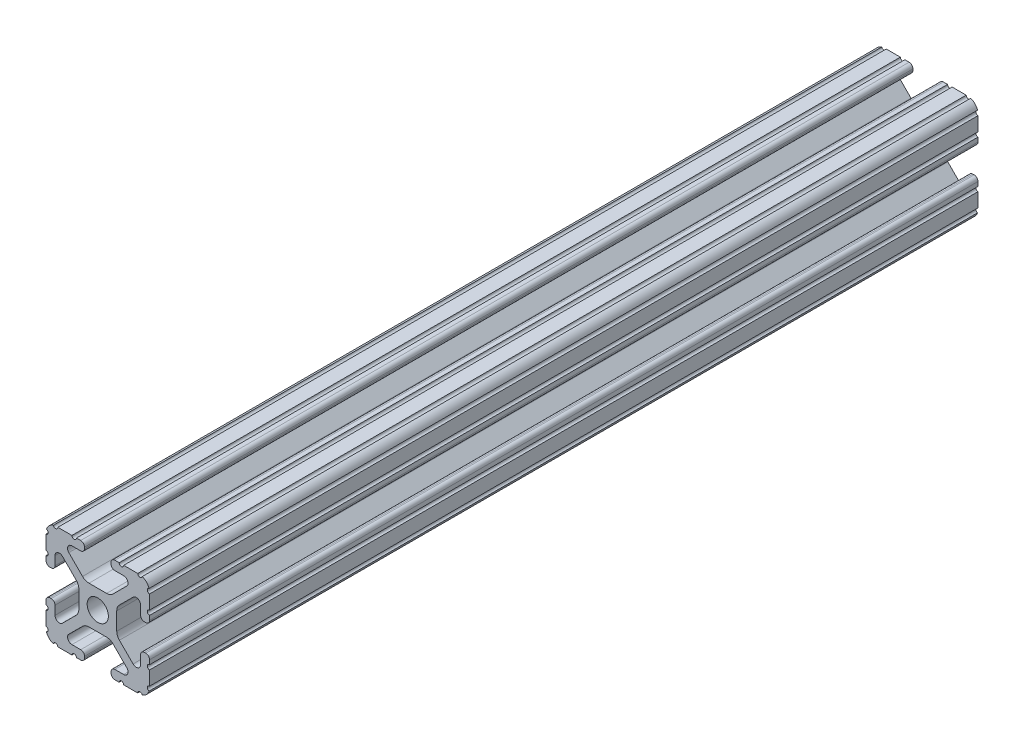
SolidWorks part; units mm, degrees
ref_plane "Front Plane" through (0, 0, 0) normal (0, 0, 1) x (1, 0, 0)
ref_plane "Top Plane" through (0, 0, 0) normal (0, 1, 0) x (1, 0, 0)
ref_plane "Right Plane" through (0, 0, 0) normal (1, 0, 0) x (0, 0, -1)
sketch "Sketch2" plane through (0, 0, 0) normal (0, 0, 1) x (1, 0, 0)
  line L0 (0, 12.7) -> (0, -12.7) construction
  line L1 (-12.7, 0) -> (12.7, 0) construction
  line L2 (3.2512, -12.7) -> (12.7, -12.7)
  line L3 (12.7, -12.7) -> (12.7, -3.2512)
  line L4 (3.2512, -12.7) -> (3.2512, -10.4902)
  line L5 (3.2512, -10.4902) -> (8.9276, -10.4902)
  line L6 (8.9276, -10.4902) -> (3.0856, -4.6482)
  line L7 (0, 0) -> (12.7, -12.7) construction
  line L8 (12.7, -3.2512) -> (10.4902, -3.2512)
  line L9 (10.4902, -3.2512) -> (10.4902, -8.9276)
  line L10 (10.4902, -8.9276) -> (4.6482, -3.0856)
  circle A0 centre (0, 0) radius 2.6035
  arc A1 (6.3485, -10.4902) -> (7.1039, -8.6665) centre (6.3485, -9.4219) ccw construction
  point P8 (0, -4.6482)
  dimension "Center Hole Diameter" = 5.207
  dimension "Rail Height" = 25.4
  dimension "Rail Width" = 25.4
  dimension "T-Slot Width" = 6.5024
  dimension "Slot Inner Width" = 14.8336
  dimension "Thickness" = 2.2098
  dimension "Slot Depth" = 5.842
  dimension "D1" = 2.2098
sketch "Sketch3" plane through (0, 0, 0) normal (1, 0, 0) x (0, 0, -1)
  line L0 (-152.4, -12.7) -> (152.4, -12.7) construction
  line L1 (-127, 0) -> (127, 0) construction
  dimension "Length" = 304.8
  dimension "D1" = 25.4
sketch "Sketch4" plane through (0, 0, 0) normal (0, 0, 1) x (1, 0, 0)
  line L0 (4.1904, -12.7) -> (10.1173, -12.7)
  line L1 (3.2512, -12.7) -> (12.7, -12.7) construction
  line L2 (3.2512, -12.7) -> (3.2512, -10.4902) construction
  line L3 (3.2512, -10.4902) -> (8.9276, -10.4902) construction
  line L4 (3.2512, -11.4294) -> (3.2512, -11.7608)
  line L5 (4.1904, -10.4902) -> (6.3485, -10.4902)
  line L6 (0, -4.6482) -> (2.164, -4.6482)
  line L7 (8.9276, -10.4902) -> (3.0856, -4.6482) construction
  line L8 (3.7373, -5.2999) -> (7.1039, -8.6665)
  line L9 (12.7, -12.7) -> (12.7, -3.2512) construction
  line L10 (10.4902, -8.9276) -> (4.6482, -3.0856) construction
  line L11 (10.4902, -3.2512) -> (10.4902, -8.9276) construction
  line L12 (10.4902, -6.3485) -> (10.4902, -4.1904)
  line L13 (12.7, -3.2512) -> (10.4902, -3.2512) construction
  line L14 (11.4294, -3.2512) -> (11.7608, -3.2512)
  line L15 (12.7, -4.1904) -> (12.7, -10.1173)
  line L16 (8.6665, -7.1039) -> (5.2999, -3.7373)
  line L17 (4.6482, 0) -> (4.6482, -2.164)
  line L18 (-12.7, 0) -> (12.7, 0) construction
  line L19 (0, -4.6482) -> (0, -2.6035)
  line L20 (0, 12.7) -> (0, -12.7) construction
  line L21 (4.6482, 0) -> (2.6035, 0)
  arc A0 (3.2512, -11.7608) -> (4.1904, -12.7) centre (4.1904, -11.7608) ccw
  arc A2 (3.2512, -11.4294) -> (4.1904, -10.4902) centre (4.1904, -11.4294) cw
  arc A3 (6.3485, -10.4902) -> (7.1039, -8.6665) centre (6.3485, -9.4219) ccw
  arc A4 (2.164, -4.6482) -> (3.7373, -5.2999) centre (2.164, -6.8732) cw
  arc A5 (10.1173, -12.7) -> (12.7, -10.1173) centre (10.1173, -10.1173) ccw
  arc A6 (8.6665, -7.1039) -> (10.4902, -6.3485) centre (9.4219, -6.3485) ccw
  arc A7 (10.4902, -4.1904) -> (11.4294, -3.2512) centre (11.4294, -4.1904) cw
  arc A8 (11.7608, -3.2512) -> (12.7, -4.1904) centre (11.7608, -4.1904) cw
  arc A9 (5.2999, -3.7373) -> (4.6482, -2.164) centre (6.8732, -2.164) cw
  circle A10 centre (0, 0) radius 2.6035 construction
  arc A11 (0, -2.6035) -> (2.6035, 0) centre (0, 0) ccw
  dimension "D1" = 2.5827
  dimension "D2" = 2.225
  dimension "D3" = 0.9392
extrude "Boss-Extrude1" add sketch "Sketch4" along normal mid plane 304.8
sketch "Sketch5" plane through (0, 0, 0) normal (0, 0, 1) x (1, 0, 0)
  line L0 (3.2512, -12.7) -> (12.7, -12.7) construction
  line L1 (4.1904, -10.4902) -> (6.3485, -10.4902) construction
  line L3 (0, 0) -> (12.7, -12.7) construction
  line L4 (6.3485, -10.4902) -> (6.3485, -12.7) construction
  line L5 (8.9276, -10.4902) -> (3.0856, -4.6482) construction
  circle A0 centre (10.3562, -12.7) radius 0.5524
  circle A1 centre (5.796, -12.7) radius 0.5524
  circle A2 centre (12.7, -10.3562) radius 0.5524
  circle A3 centre (12.7, -5.796) radius 0.5524
  point P10 (5.2694, -10.4902)
  point P12 (9.4219, -6.3485)
  dimension "D1" = 1.1049
extrude "Cut-Extrude1" cut sketch "Sketch5" against normal through all both and the other way through all
mirror "Mirror1" about plane through (0, 0, 0) normal (1, 0, 0) of bodies 137 134
mirror "Mirror2" about plane through (0, 0, 0) normal (0, 1, 0) of bodies 135
sketch "Sketch6" plane through (12.7, 0, 0) normal (1, 0, 0) x (0, 0, -1)
  line L0 (152.4, -12.7) -> (-152.4, -12.7) construction
  line L1 (-152.4, 12.7) -> (-101.6, 12.7)
  line L2 (-152.4, 12.7) -> (-152.4, -12.7)
  line L3 (-152.4, -12.7) -> (-101.6, -12.7)
  line L4 (-101.6, 12.7) -> (-101.6, -12.7)
  line L5 (152.4, 12.7) -> (-152.4, 12.7) construction
  line L6 (152.4, -12.7) -> (101.6, -12.7)
  line L7 (152.4, -12.7) -> (152.4, 12.7)
  line L8 (152.4, 12.7) -> (101.6, 12.7)
  line L9 (101.6, -12.7) -> (101.6, 12.7)
  dimension "D1" = 50.8
  dimension "D2" = 50.8
extrude "Cut-Extrude2" cut sketch "Sketch6" against normal through all
equation "\"D1@Boss-Extrude1\"=\"Length@Sketch3\""
equation "\"D1@Sketch2\"=\"Thickness@Sketch2\""
equation "\"D2@Sketch4\"=\"Slot Inner Width@Sketch2\"*0.15"
equation "\"D1@Sketch4\"=\"D3@Sketch4\"*2.75"
equation "\"D3@Sketch4\"=\"Thickness@Sketch2\"*0.425"
equation "\"D1@Sketch5\"=\"Thickness@Sketch2\"*0.5"
